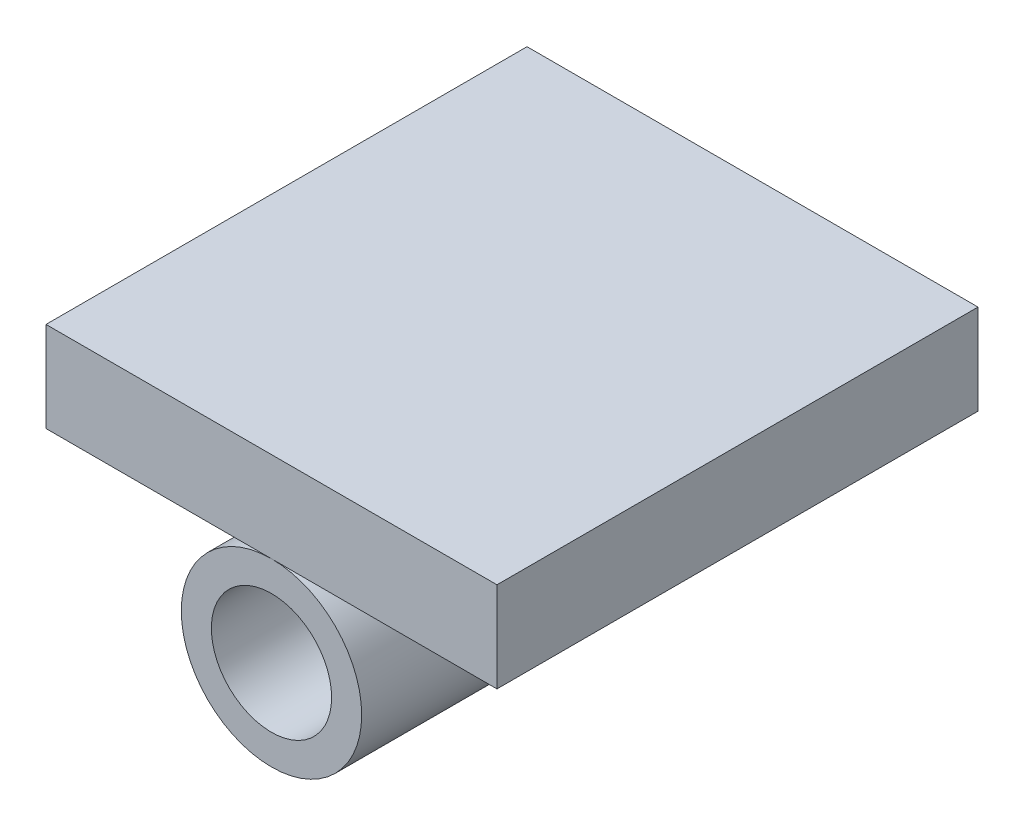
SolidWorks part; units mm, degrees
ref_plane "Front Plane" through (0, 0, 0) normal (0, 0, 1) x (1, 0, 0)
ref_plane "Top Plane" through (0, 0, 0) normal (0, 1, 0) x (1, 0, 0)
ref_plane "Right Plane" through (0, 0, 0) normal (1, 0, 0) x (0, 0, -1)
sketch "Sketch1" plane through (0, 0, 0) normal (0, 0, 1) x (1, 0, 0)
  circle A0 centre (0, 0) radius 20
  circle A1 centre (0, 0) radius 30
  dimension "D1" = 60
  dimension "D2" = 40
extrude "Boss-Extrude1" add sketch "Sketch1" along normal mid plane 160
ref_plane "Plane1" through (0, 30, 0) normal (0, 1, 0) x (1, 0, 0)
sketch "Sketch2" plane through (0, 30, 0) normal (0, 1, 0) x (1, 0, 0)
  line L0 (30, 80) -> (-30, 80) construction
  line L1 (-75, 80) -> (75, 80)
  line L2 (-75, 80) -> (-75, -80)
  line L3 (-75, -80) -> (75, -80)
  line L4 (75, 80) -> (75, -80)
  dimension "D1" = 75
  dimension "D2" = 75
  dimension "D3" = 160
extrude "Boss-Extrude2" add sketch "Sketch2" along normal blind 30 separate body
